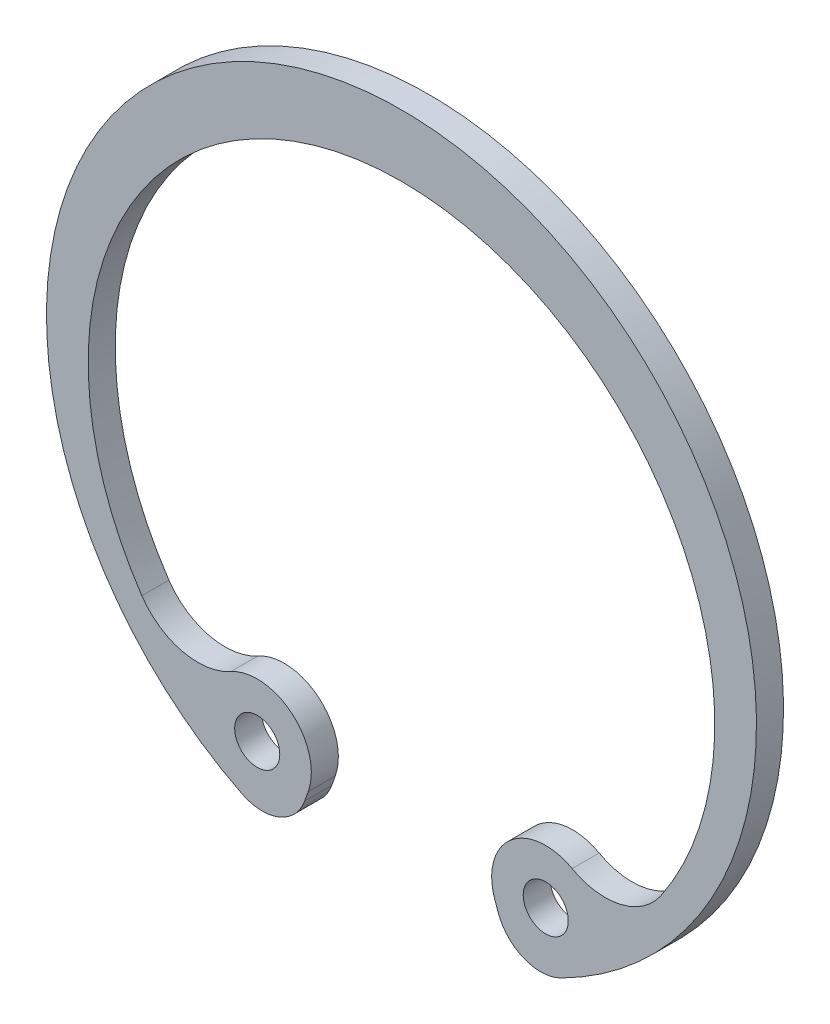
SolidWorks part; units mm, degrees
ref_plane "Спереди" through (0, 0, 0) normal (0, 0, 1) x (1, 0, 0)
ref_plane "Сверху" through (0, 0, 0) normal (0, 1, 0) x (1, 0, 0)
ref_plane "Справа" through (0, 0, 0) normal (1, 0, 0) x (0, 0, -1)
sketch "Clipboard" plane through (0, 0, 0) normal (0, 0, 1) x (1, 0, 0)
  circle A0 centre (0, 0) radius 15
  dimension "D1" = 30
sketch "Sketch1" plane through (0, 0, 0) normal (0, 0, 1) x (1, 0, 0)
  line L0 (0, -32.7005) -> (0, 29.6631) construction
  line L1 (4.1391, -11.6212) -> (4.2937, -12.0551)
  line L4 (-4.1391, -11.6212) -> (-4.2937, -12.0551)
  line L5 (0, 0) -> (-6.2395, -17.5183) construction
  arc A0 (-7.0763, -13.1708) -> (7.0763, -13.1708) centre (0, 0.9) cw
  arc A1 (-7.0763, -13.1708) -> (-4.2937, -12.0551) centre (-6.1777, -11.3841) ccw
  arc A2 (-7.5506, -12.9221) -> (-4.1391, -11.6212) centre (-6.4, -10.8159) ccw construction
  arc A3 (-11.5186, -7.7803) -> (-7.57, -8.7204) centre (-9.0325, -6.1011) ccw
  arc A4 (7.0763, -13.1708) -> (4.2937, -12.0551) centre (6.1777, -11.3841) cw
  arc A5 (4.1391, -11.6212) -> (7.57, -8.7204) centre (6.4, -10.8159) cw
  arc A6 (11.5186, -7.7803) -> (7.57, -8.7204) centre (9.0325, -6.1011) cw
  arc A7 (-4.1391, -11.6212) -> (-7.57, -8.7204) centre (-6.4, -10.8159) ccw
  circle A8 centre (-6.4, -10.8159) radius 1
  circle A9 centre (6.4, -10.8159) radius 1
  arc A11 (11.5186, -7.7803) -> (-11.5186, -7.7803) centre (0, 0) ccw
  point P15 (-8.7994, -10.7602)
  dimension "D2" = 27.8
  dimension "D3" = 31.5
  dimension "D4" = 2
  dimension "R1" = 3
  dimension "R2" = 2
  dimension "a" = 4.8
  dimension "L" = 8
  dimension "e" = 0.9
  dimension "b" = 2.75
extrude "Body" add sketch "Sketch1" along normal blind 1.2
